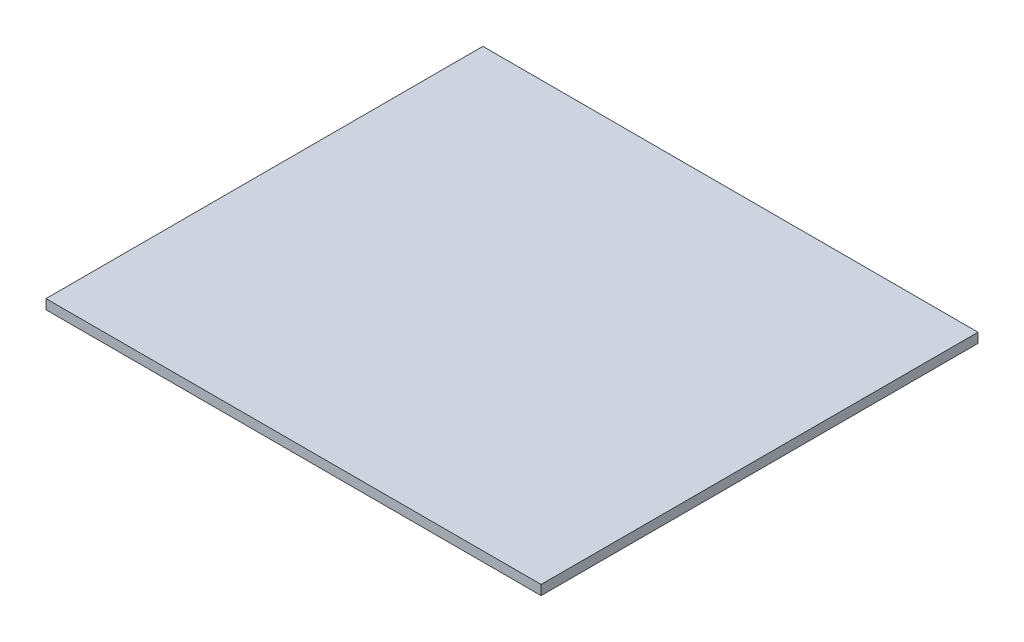
SolidWorks part; units mm, degrees
ref_plane "前视基准面" through (0, 0, 0) normal (0, 0, 1) x (1, 0, 0)
ref_plane "上视基准面" through (0, 0, 0) normal (0, 1, 0) x (1, 0, 0)
ref_plane "右视基准面" through (0, 0, 0) normal (1, 0, 0) x (0, 0, -1)
other "Configuration Table"
sketch "Sketch1" plane through (0, 0, 0) normal (0, 1, 0) x (1, 0, 0)
  line L1 (51, -45) -> (-51, -45)
  line L2 (51, -45) -> (51, 45)
  line L3 (51, 45) -> (-51, 45)
  line L4 (-51, -45) -> (-51, 45)
  line L5 (51, -45) -> (-51, 45) construction
  line L6 (51, 45) -> (-51, -45) construction
  point P0 (0, 0)
  dimension "D1" = 90
  dimension "D2" = 102
extrude "Boss-Extrude1" add sketch "Sketch1" along normal blind 2
